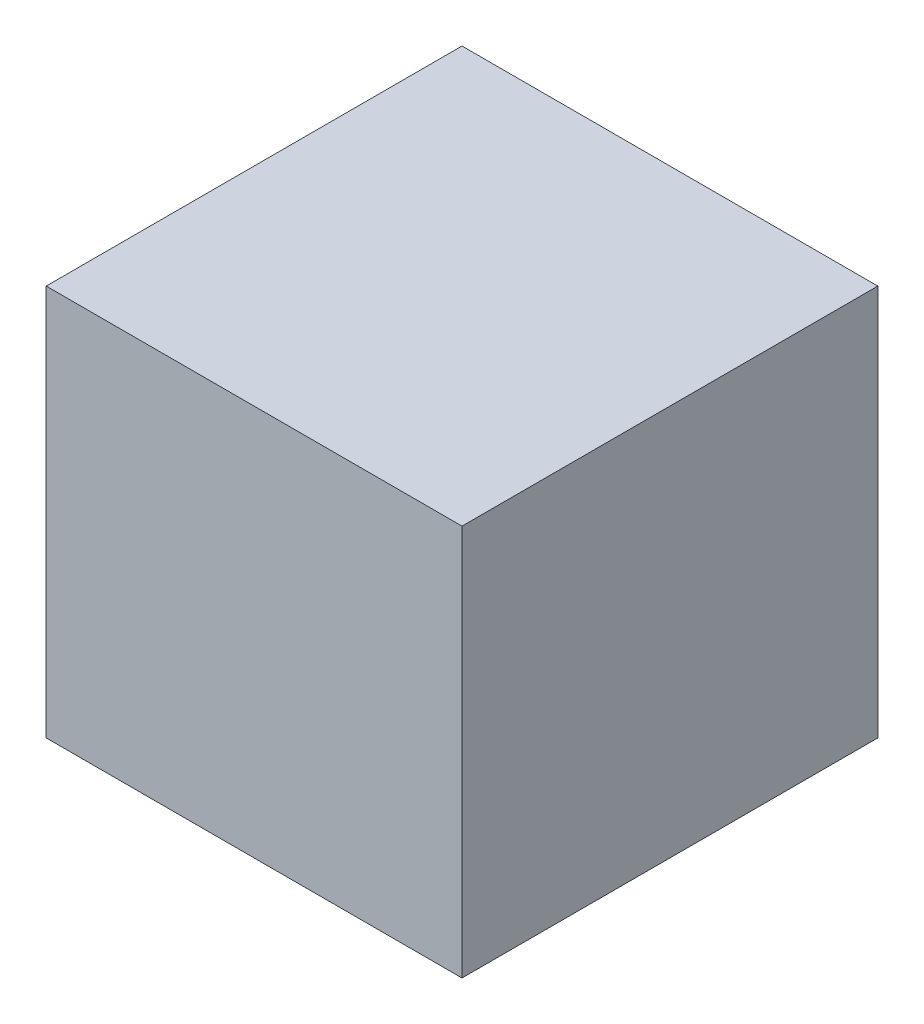
SolidWorks part; units mm, degrees
ref_plane "Front Plane" through (0, 0, 0) normal (0, 0, 1) x (1, 0, 0)
ref_plane "Top Plane" through (0, 0, 0) normal (0, 1, 0) x (1, 0, 0)
ref_plane "Right Plane" through (0, 0, 0) normal (1, 0, 0) x (0, 0, -1)
sketch "Sketch1" plane through (0, 0, 0) normal (0, 1, 0) x (1, 0, 0)
  line L1 (-42.5, -42.5) -> (42.5, -42.5)
  line L2 (-42.5, -42.5) -> (-42.5, 42.5)
  line L3 (-42.5, 42.5) -> (42.5, 42.5)
  line L4 (42.5, -42.5) -> (42.5, 42.5)
  line L5 (-42.5, -42.5) -> (42.5, 42.5) construction
  line L6 (-42.5, 42.5) -> (42.5, -42.5) construction
  point P0 (0, 0)
  dimension "D1" = 85
extrude "Boss-Extrude1" add sketch "Sketch1" along normal blind 80
